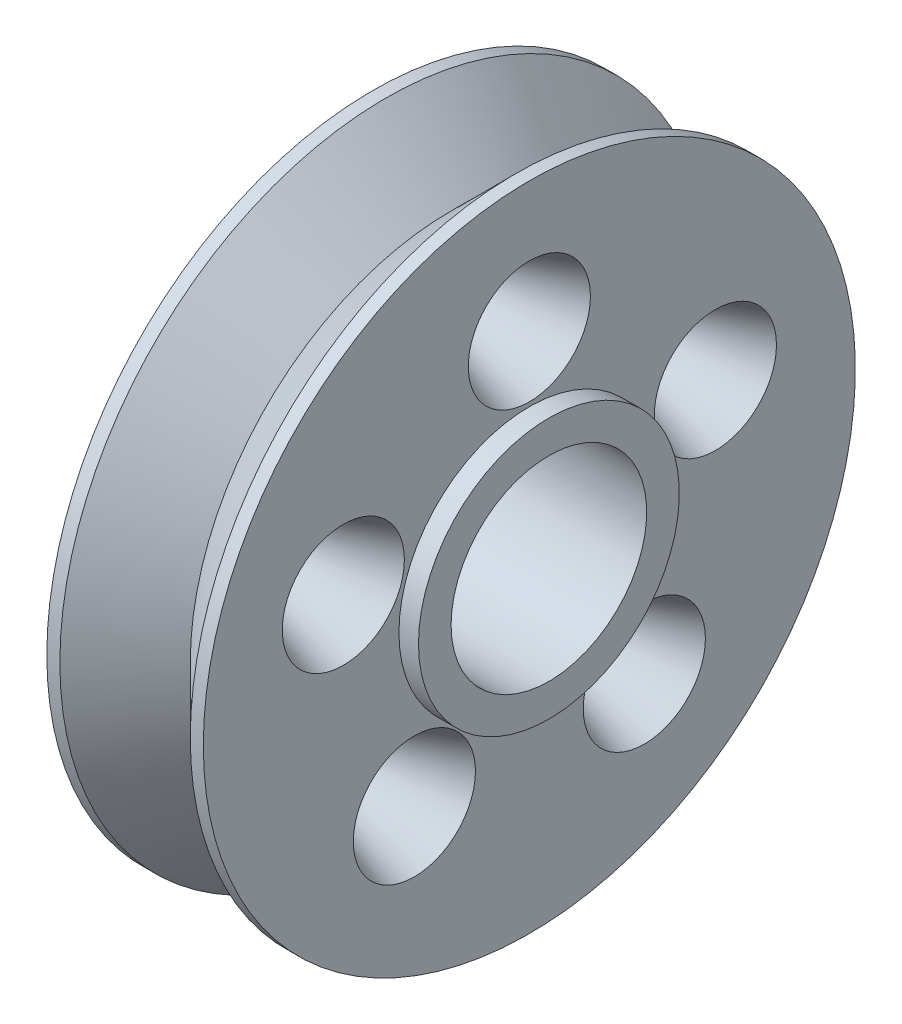
SolidWorks part; units mm, degrees
ref_plane "Ön Düzlem" through (0, 0, 0) normal (0, 0, 1) x (1, 0, 0)
ref_plane "Üst Düzlem" through (0, 0, 0) normal (0, 1, 0) x (1, 0, 0)
ref_plane "Sağ Düzlem" through (0, 0, 0) normal (1, 0, 0) x (0, 0, -1)
sketch "Çizim1" plane through (0, 0, 0) normal (0, 0, 1) x (1, 0, 0)
  line L0 (-17.6767, 0) -> (30.5114, 0) construction
  line L1 (-10.1366, 50) -> (-0.1366, 40)
  line L2 (-12.1366, 50) -> (-10.1366, 50)
  line L3 (-12.1366, 50) -> (-12.1366, 20)
  line L4 (-12.1366, 15) -> (11.8634, 15)
  line L5 (11.8634, 50) -> (11.8634, 20)
  line L6 (-0.1366, 40) -> (9.8634, 50)
  line L7 (9.8634, 50) -> (11.8634, 50)
  line L9 (-12.1366, 15) -> (-15.1366, 15)
  line L11 (-12.1366, 20) -> (-15.1366, 20)
  line L12 (-15.1366, 15) -> (-15.1366, 20)
  line L13 (11.8634, 15) -> (14.8634, 15)
  line L15 (11.8634, 20) -> (14.8634, 20)
  line L16 (14.8634, 15) -> (14.8634, 20)
  point P9 (-0.1366, 15)
  dimension "D1" = 15
  dimension "D2" = 50
  dimension "D3" = 24
  dimension "D4" = 25
  dimension "D5" = 135
  dimension "D6" = 90
  dimension "D7" = 25
  dimension "D8" = 10
  dimension "D9" = 3
  dimension "D10" = 3
  dimension "D11" = 20
  dimension "D12" = 20
revolve "Döndür1" add sketch "Çizim1" angle 360 about L0
ref_plane "Düzlem1" through (-0.1366, 0, 0) normal (1, 0, 0) x (0, 0, -1)
sketch "Çizim2" plane through (-0.1366, 0, 0) normal (1, 0, 0) x (0, 0, -1)
  circle A0 centre (0, 30) radius 5
  dimension "D1" = 10
  dimension "D2" = 30
extrude "Kes-Ekstrüzyon3" cut sketch "Çizim2" against normal blind 12 draft 20 and the other way blind 12 draft 20 contours A0
pattern_circular "Dairesel Kaplama1" count 5 over 360 about axis through (0, 0, 0) along (1, 0, 0) of "Kes-Ekstrüzyon3"
